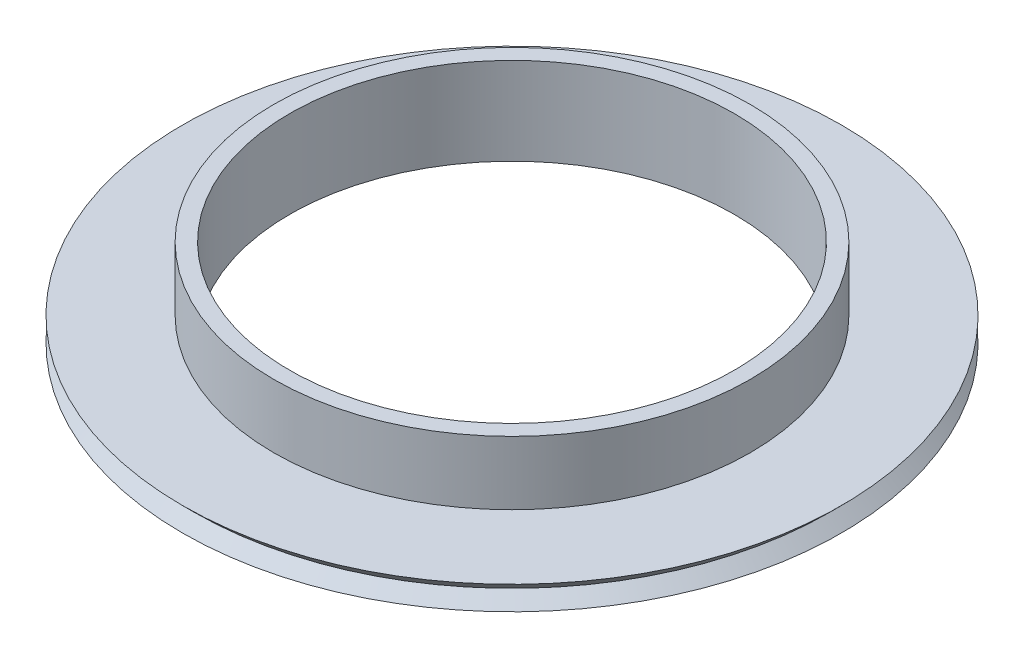
SolidWorks part; units mm, degrees
ref_plane "Front Plane" through (0, 0, 0) normal (0, 0, 1) x (1, 0, 0)
ref_plane "Top Plane" through (0, 0, 0) normal (0, 1, 0) x (1, 0, 0)
ref_plane "Right Plane" through (0, 0, 0) normal (1, 0, 0) x (0, 0, -1)
sketch "Sketch1" plane through (0, 0, 0) normal (0, 0, 1) x (1, 0, 0)
  line L0 (0, 0) -> (0, 123.2609) construction
  line L1 (-28, 11) -> (-28, 0)
  line L2 (-28, 0) -> (-41.5, 0)
  line L3 (-41.5, 0) -> (-40, 1.5)
  line L4 (-40, 1.5) -> (-41.5, 3)
  line L5 (-41.5, 3) -> (-30, 3)
  line L7 (-28, 11) -> (-30, 11)
  line L8 (-30, 11) -> (-30, 3)
  point P3 (-28, 11)
  point P5 (0, 0)
  dimension "D1" = 56
  dimension "D2" = 80
  dimension "D3" = 3
  dimension "D4" = 2
  dimension "D5" = 8
  dimension "D6" = 45
revolve "Revolve1" add sketch "Sketch1" angle 360 about L0
